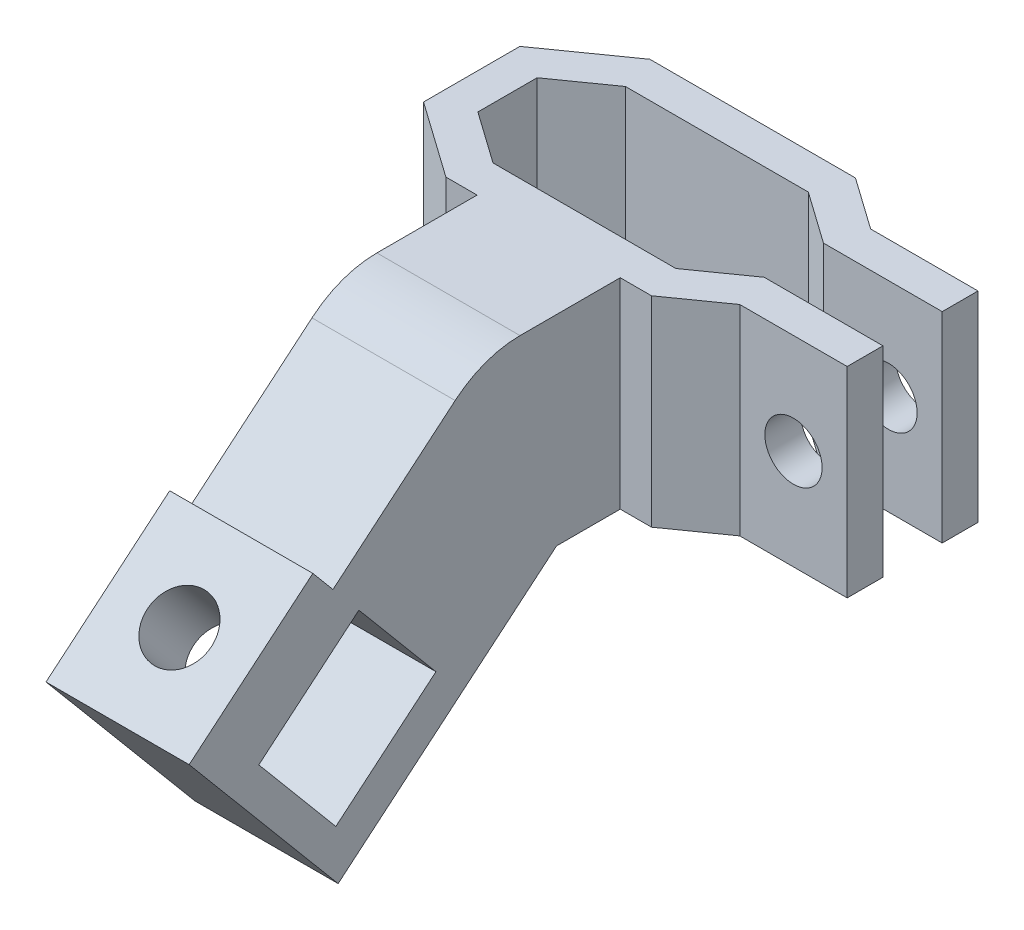
SolidWorks part; units mm, degrees
ref_plane "Front Plane" through (0, 0, 0) normal (0, 0, 1) x (1, 0, 0)
ref_plane "Top Plane" through (0, 0, 0) normal (0, 1, 0) x (1, 0, 0)
ref_plane "Right Plane" through (0, 0, 0) normal (1, 0, 0) x (0, 0, -1)
sketch "Sketch1" plane through (0, 0, 0) normal (0, 1, 0) x (1, 0, 0)
  line L1 (-6.4878, -4.699) -> (6.4878, -4.699)
  line L2 (-10.16, -2.1026) -> (-10.16, 2.1026)
  line L3 (-6.4878, 4.699) -> (6.4878, 4.699)
  line L5 (0, -11.84) -> (0, 9.1105) construction
  line L6 (10.16, -2.1026) -> (6.4878, -4.699)
  line L12 (10.16, 2.1026) -> (6.4878, 4.699)
  line L14 (-13.446, 0) -> (15.0887, 0) construction
  line L15 (-10.16, 2.1026) -> (-6.4878, 4.699)
  line L18 (-7.2951, -7.239) -> (7.2951, -7.239)
  line L21 (-10.16, -2.1026) -> (-6.4878, -4.699)
  line L22 (10.9673, -4.6426) -> (7.2951, -7.239)
  line L24 (10.9673, 4.6426) -> (7.2951, 7.239)
  line L25 (-7.2951, 7.239) -> (7.2951, 7.239)
  line L26 (-12.7, 3.4175) -> (-7.2951, 7.239)
  line L27 (-12.7, -3.4175) -> (-12.7, 3.4175)
  line L28 (-12.7, -3.4175) -> (-7.2951, -7.239)
  line L29 (10.16, 2.1026) -> (18.5873, 2.1026)
  line L30 (18.5873, 2.1026) -> (18.5873, 4.6426)
  line L31 (18.5873, 4.6426) -> (10.9673, 4.6426)
  line L32 (10.16, -2.1026) -> (18.5873, -2.1026)
  line L33 (18.5873, -2.1026) -> (18.5873, -4.6426)
  line L34 (18.5873, -4.6426) -> (10.9673, -4.6426)
  line L35 (12.7, -3.4175) -> (12.7, 3.4175) construction
  line L36 (12.7, 3.4175) -> (7.2951, 7.239) construction
  line L37 (10.16, -2.1026) -> (10.16, 2.1026) construction
  line L38 (12.7, -3.4175) -> (7.2951, -7.239) construction
  point P0 (0, 0)
  point P39 (9.906, 0)
  point P40 (9.906, 0)
  dimension "D3" = 2.54
  dimension "D2" = 9.398
  dimension "D4" = 7.62
  dimension "D5" = 2.54
extrude "Boss-Extrude1" add sketch "Sketch1" along normal blind 14.224
sketch "Sketch2" plane through (0, 0, 7.239) normal (0, 0, 1) x (1, 0, 0)
  line L3 (-7.2951, 14.224) -> (7.2951, 14.224) construction
  line L4 (-5.08, 14.224) -> (5.08, 14.224)
  line L9 (-5.08, 14.224) -> (-5.08, 0)
  line L10 (-7.2951, 0) -> (7.2951, 0) construction
  line L11 (-5.08, 0) -> (5.08, 0)
  line L12 (5.08, 0) -> (5.08, 14.224)
  point P0 (0, 0)
  point P5 (0, 0)
  dimension "D1" = 10.16
extrude "Boss-Extrude2" add sketch "Sketch2" along normal blind 7.112
sketch "Sketch3" plane through (0, 0, 14.351) normal (0, 0, 1) x (1, 0, 0)
  line L0 (-5.08, 7.112) -> (5.08, 7.112)
  line L1 (-5.08, 14.224) -> (-5.08, 0) construction
  line L2 (5.08, 0) -> (5.08, 14.224) construction
  line L3 (5.08, 7.112) -> (5.08, 14.224)
  line L4 (5.08, 14.224) -> (-5.08, 14.224) construction
  line L5 (5.08, 14.224) -> (-5.08, 14.224)
  line L6 (-5.08, 14.224) -> (-5.08, 7.112)
revolve "Revolve2" add sketch "Sketch3" angle 180 about L0
sketch "Sketch5" plane through (0, 0, -4.6426) normal (0, 0, -1) x (-1, 0, 0)
  circle A0 centre (-14.7773, 7.112) radius 2.032
extrude "Cut-Extrude2" cut sketch "Sketch5" against normal up to surface (9.2852 mm away) up to face at (14.7773, 7.112, 4.6426)
sketch "Sketch7" plane through (5.08, 0, 0) normal (1, 0, 0) x (0, 0, -1)
  line L0 (-27.26, -13.0038) -> (-36.4028, -2.1078)
  line L1 (-18.8911, 12.5863) -> (-27.6254, 5.2573)
  line L2 (-9.7482, 1.6903) -> (-27.26, -13.0038)
  line L3 (-18.8911, 12.5863) -> (-9.7482, 1.6903)
  line L5 (-27.4213, -9.4091) -> (-32.8907, -2.8908)
  line L6 (-25.7887, 3.0684) -> (-20.3193, -3.4498)
  line L7 (-32.8907, -2.8908) -> (-25.7887, 3.0684)
  line L8 (-27.4213, -9.4091) -> (-20.3193, -3.4498)
  line L9 (-27.6254, 5.2573) -> (-29.0541, 6.96)
  line L12 (-36.4028, -2.1078) -> (-37.8315, -0.4052)
  line L13 (-29.0541, 6.96) -> (-37.8315, -0.4052)
  circle A0 centre (-14.351, 7.112) radius 7.112
  dimension "D1" = 8.509
  dimension "D2" = 9.271
  dimension "D3" = 2.8574
extrude "Boss-Extrude4" add sketch "Sketch7" against normal up to surface (10.16 mm away) contours L2 L3 L1 L9 L13 L12 L0 | L6 L8 L5 L7 up to face at (-5.08, 7.112, 12.573)
sketch "Sketch8" plane through (0, 18.3906, 15.4316) normal (0, 0.766, 0.6428) x (1, 0, 0)
  line L0 (0, -14.9753) -> (0, 14.9753) construction
  circle A0 centre (0, -23.512) radius 2.286
  dimension "D1" = 4.572
extrude "Cut-Extrude3" cut sketch "Sketch8" against normal up to surface (5.08 mm away) up to face at (0, 0.0888, 29.3397)
